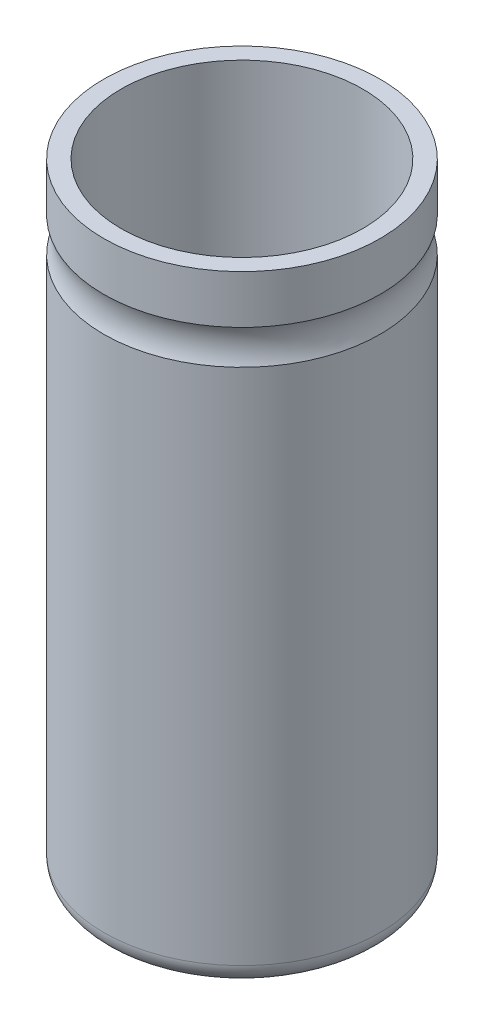
SolidWorks part; units mm, degrees
ref_plane "Front Plane" through (0, 0, 0) normal (0, 0, 1) x (1, 0, 0)
ref_plane "Top Plane" through (0, 0, 0) normal (0, 1, 0) x (1, 0, 0)
ref_plane "Right Plane" through (0, 0, 0) normal (1, 0, 0) x (0, 0, -1)
sketch "Sketch7" plane through (0, 0, 0) normal (0, 0, 1) x (1, 0, 0)
  line L0 (0, 0) -> (20000, 0)
  line L1 (20000, 0) -> (20000, 78000)
  line L2 (17500, 90000) -> (20000, 90000)
  line L3 (17500, 90000) -> (17500, 3000)
  line L4 (17500, 3000) -> (0, 3000)
  line L5 (0, 3000) -> (0, 0)
  line L6 (20000, 83000) -> (20000, 90000)
  arc A0 (20000, 83000) -> (20000, 78000) centre (25454.3561, 80500) ccw
  point P10 (0, 0)
  dimension "D7" = 6000
  dimension "D1" = 3000
  dimension "D2" = 90000
  dimension "D3" = 2500
  dimension "D4" = 20000
  dimension "D5" = 7000
  dimension "D6" = 5000
revolve "Revolve1" add sketch "Sketch7" angle 360 about L5
fillet "Fillet4" radius 3000 1 edges at (0, 0, 20000)
